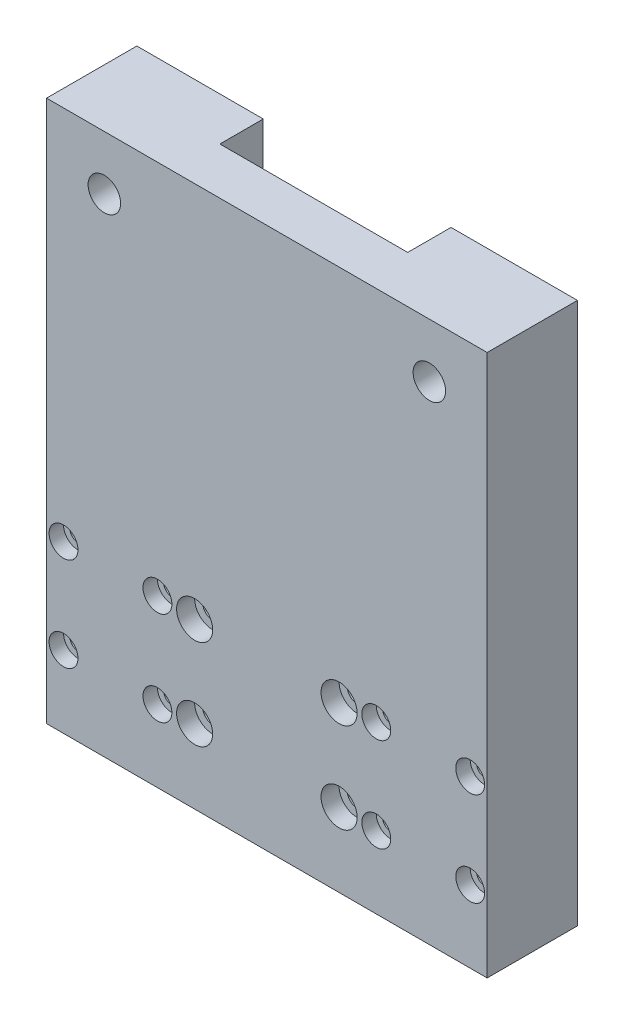
SolidWorks part; units mm, degrees
ref_plane "Front Plane" through (0, 0, 0) normal (0, 0, 1) x (1, 0, 0)
ref_plane "Top Plane" through (0, 0, 0) normal (0, 1, 0) x (1, 0, 0)
ref_plane "Right Plane" through (0, 0, 0) normal (1, 0, 0) x (0, 0, -1)
sketch "Sketch1" plane through (0, 0, 0) normal (0, 0, 1) x (1, 0, 0)
  line L1 (0, 0) -> (122, 0)
  line L2 (0, 0) -> (0, 150)
  line L3 (0, 150) -> (122, 150)
  line L4 (122, 0) -> (122, 150)
  dimension "D1" = 122
  dimension "D2" = 150
extrude "Boss-Extrude1" add sketch "Sketch1" along normal blind 25
sketch "Sketch2" plane through (0, 0, 25) normal (0, 0, 1) x (1, 0, 0)
  line L0 (61, 150) -> (61, 0) construction
  line L1 (122, 150) -> (0, 150) construction
  line L2 (0, 0) -> (122, 0) construction
  line L3 (0, 33) -> (122, 33) construction
  line L4 (0, 150) -> (0, 0) construction
  line L5 (122, 0) -> (122, 150) construction
  point P6 (30.7, 20)
  point P7 (30.7, 46)
  point P8 (4.7, 20)
  point P9 (4.7, 46)
  point P10 (117.3, 46)
  point P11 (117.3, 20)
  point P12 (91.3, 46)
  point P13 (91.3, 20)
  point P20 (41, 45.5)
  point P21 (81, 45.5)
  point P22 (81, 20.5)
  point P23 (41, 20.5)
  dimension "D1" = 30.3
  dimension "D2" = 26
  dimension "D3" = 26
  dimension "D4" = 20
  dimension "D5" = 13
  dimension "D6" = 12.5
  dimension "D7" = 20
hole_wizard "CBORE for M4 SHCS1" positions "3DSketch1" profile "Sketch3" counterbore size "M4" standard "ANSI Metric" end condition through all
sketch3d "3DSketch1"
  point P0 (4.7, 46, 25)
  point P3 (30.7, 46, 25)
  point P6 (4.7, 20, 25)
  point P9 (30.7, 20, 25)
  point P12 (91.3, 46, 25)
  point P15 (117.3, 46, 25)
  point P18 (117.3, 20, 25)
  point P21 (91.3, 20, 25)
sketch "Sketch3" plane through (4.7, 46, 25) normal (1, 0, 0) x (0, -1, 0)
  line L0 (0, 0) -> (0, 25)
  line L1 (0, 25) -> (2.25, 25)
  line L3 (2.25, 25) -> (2.25, 4)
  line L4 (2.25, 4) -> (4, 4)
  line L5 (4, 4) -> (4, 0)
  line L7 (4, 0) -> (0, 0)
  line L11 (0, -6.35) -> (0, 107.95) construction
  dimension "Thru Hole Dia." = 4.5
  dimension "Thru Hole Depth" = 25
  dimension "C'Bore Dia." = 8
  dimension "C'Bore Depth" = 4
sketch "Sketch4" plane through (0, 0, 0) normal (0, 1, 0) x (1, 0, 0)
  line L0 (61, 0) -> (61, -20.062) construction
  line L1 (122, 0) -> (0, 0) construction
  line L2 (35, 0) -> (35, -12)
  line L3 (35, -12) -> (87, -12)
  line L4 (87, 0) -> (87, -12)
  line L5 (35, 0) -> (87, 0)
  point P8 (61, -12)
  dimension "D1" = 26
  dimension "D2" = 12
extrude "Cut-Extrude1" cut sketch "Sketch4" along normal through all
hole_wizard "CBORE for M5 SHCS1" positions "3DSketch3" profile "Sketch7" counterbore size "M5" standard "ANSI Metric" end condition through all
sketch3d "3DSketch3"
  point P0 (41, 45.5, 25)
  point P3 (81, 45.5, 25)
  point P6 (81, 20.5, 25)
  point P9 (41, 20.5, 25)
sketch "Sketch7" plane through (41, 45.5, 25) normal (1, 0, 0) x (0, -1, 0)
  line L0 (0, 0) -> (0, 25)
  line L1 (0, 25) -> (2.75, 25)
  line L3 (2.75, 25) -> (2.75, 5)
  line L4 (2.75, 5) -> (5, 5)
  line L5 (5, 5) -> (5, 0)
  line L7 (5, 0) -> (0, 0)
  line L11 (0, -6.35) -> (0, 107.95) construction
  dimension "Thru Hole Dia." = 5.5
  dimension "Thru Hole Depth" = 25
  dimension "C'Bore Dia." = 10
  dimension "C'Bore Depth" = 5
sketch "Sketch8" plane through (0, 0, 0) normal (0, 0, -1) x (-1, 0, 0)
  line L0 (-87, 135) -> (-35, 135) construction
  line L1 (-87, 0) -> (-87, 150) construction
  line L2 (-35, 0) -> (-35, 150) construction
  line L3 (-35, 150) -> (-87, 150) construction
  line L4 (-61, 150) -> (-61, 0) construction
  line L5 (-61, 150) -> (-61, 122.8733) construction
  point P8 (-106, 135)
  point P14 (-16, 135)
  dimension "D1" = 15
  dimension "D2" = 45
hole_wizard "CBORE for M8 SHCS1" positions "3DSketch5" profile "Sketch10" counterbore size "M8" standard "ANSI Metric" end condition through all
sketch3d "3DSketch5"
  point P0 (106, 135, 0)
  point P3 (16, 135, 0)
sketch "Sketch10" plane through (106, 135, 0) normal (1, 0, 0) x (0, 1, 0)
  line L0 (0, 0) -> (0, 25)
  line L1 (0, 25) -> (4.5, 25)
  line L3 (4.5, 25) -> (4.5, 8)
  line L4 (4.5, 8) -> (7.5, 8)
  line L5 (7.5, 8) -> (7.5, 0)
  line L7 (7.5, 0) -> (0, 0)
  line L11 (0, -6.35) -> (0, 107.95) construction
  dimension "Thru Hole Dia." = 9
  dimension "Thru Hole Depth" = 25
  dimension "C'Bore Dia." = 15
  dimension "C'Bore Depth" = 8
